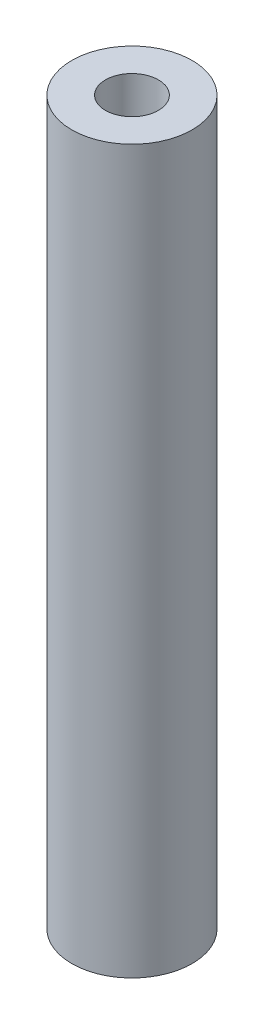
SolidWorks part; units mm, degrees
ref_plane "前视基准面" through (0, 0, 0) normal (0, 0, 1) x (1, 0, 0)
ref_plane "上视基准面" through (0, 0, 0) normal (0, 1, 0) x (1, 0, 0)
ref_plane "右视基准面" through (0, 0, 0) normal (1, 0, 0) x (0, 0, -1)
sketch "草图1" plane through (0, 0, 0) normal (0, 1, 0) x (1, 0, 0)
  circle A0 centre (0, 0) radius 2.2
  circle A1 centre (0, 0) radius 5
  dimension "D1" = 4.4
  dimension "D2" = 10
extrude "凸台-拉伸1" add sketch "草图1" along normal blind 60
